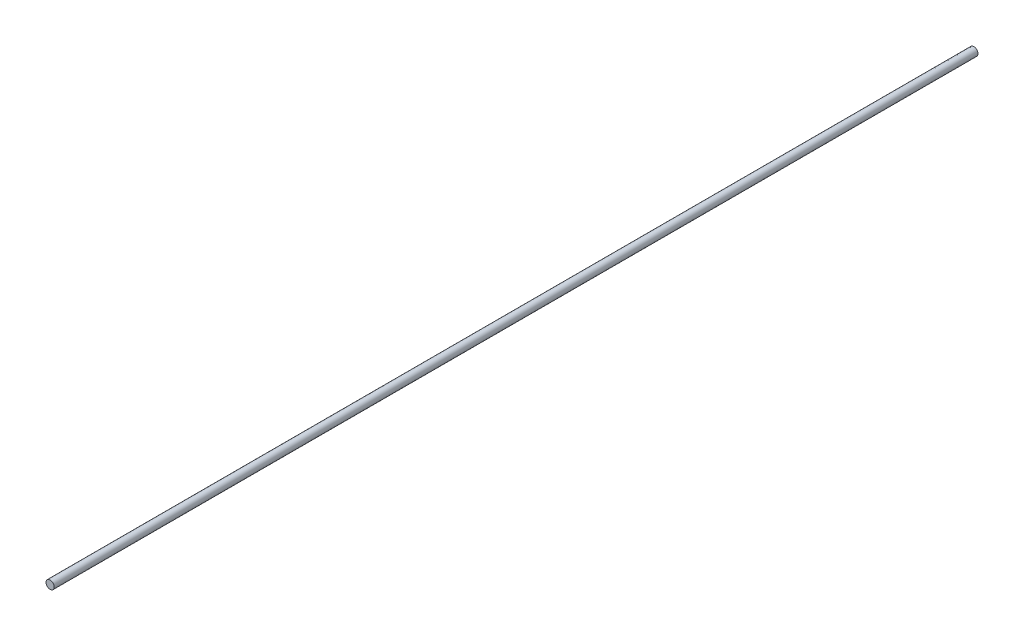
SolidWorks part; units mm, degrees
ref_plane "Front Plane" through (0, 0, 0) normal (0, 0, 1) x (1, 0, 0)
ref_plane "Top Plane" through (0, 0, 0) normal (0, 1, 0) x (1, 0, 0)
ref_plane "Right Plane" through (0, 0, 0) normal (1, 0, 0) x (0, 0, -1)
sketch "Sketch1" plane through (0, 0, 0) normal (0, 0, 1) x (1, 0, 0)
  circle A0 centre (0, 0) radius 2.5
  dimension "D1" = 5
extrude "Boss-Extrude1" add sketch "Sketch1" along normal blind 563
